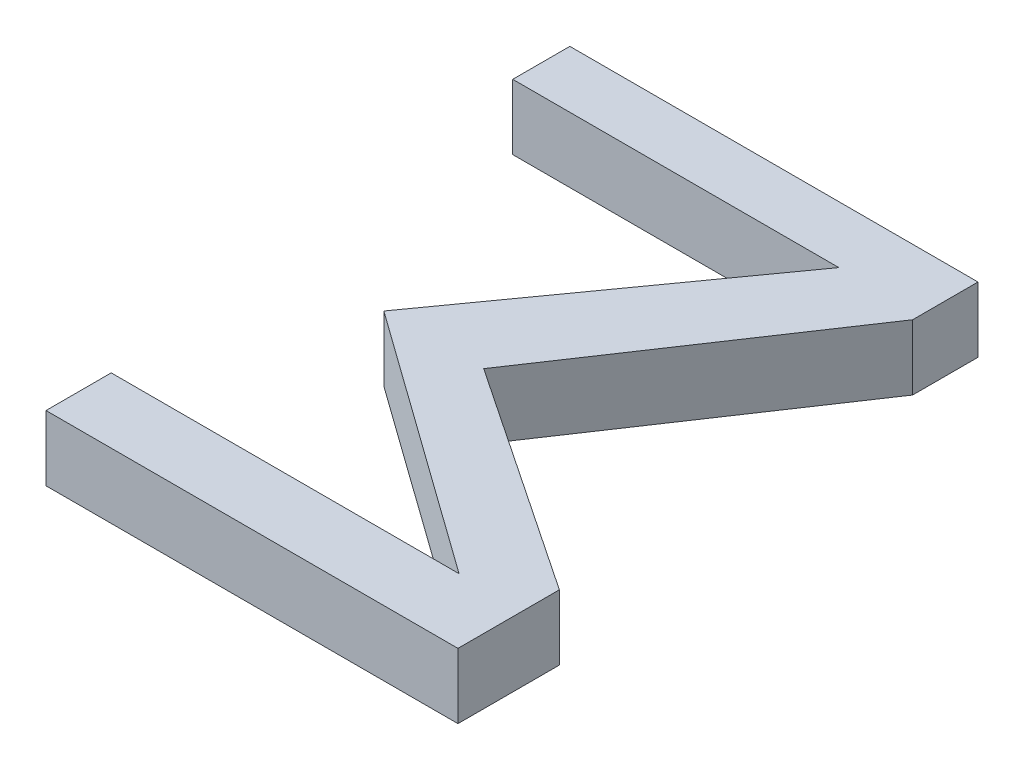
SolidWorks part; units mm, degrees
ref_plane "Front Plane" through (0, 0, 0) normal (0, 0, 1) x (1, 0, 0)
ref_plane "Top Plane" through (0, 0, 0) normal (0, 1, 0) x (1, 0, 0)
ref_plane "Right Plane" through (0, 0, 0) normal (1, 0, 0) x (0, 0, -1)
sketch "Sketch1" plane through (0, 0, 0) normal (0, 1, 0) x (1, 0, 0)
  line L0 (-6.2649, 12.1942) -> (8.7351, 12.1942)
  line L1 (8.7351, 12.1942) -> (0, 0)
  line L2 (0, 0) -> (12.1942, -8.7351)
  line L3 (12.1942, -8.7351) -> (-3.8058, -8.7351)
  line L4 (-3.8058, -8.7351) -> (-3.8058, -11.7351)
  line L5 (-3.8058, -11.7351) -> (15.1435, -11.7351)
  line L6 (15.1435, -11.7351) -> (15.1435, -7.07)
  line L7 (15.1435, -7.07) -> (4.5933, 0)
  line L8 (4.5933, 0) -> (12.5103, 11.8142)
  line L9 (12.5103, 11.8142) -> (12.5103, 14.8206)
  line L10 (12.5103, 14.8206) -> (-6.2649, 14.8206)
  line L11 (-6.2649, 14.8206) -> (-6.2649, 12.1942)
  dimension "D1" = 15
  dimension "D2" = 15
  dimension "D3" = 15
  dimension "D4" = 16
  dimension "D5" = 3
extrude "Boss-Extrude1" add sketch "Sketch1" along normal blind 3
